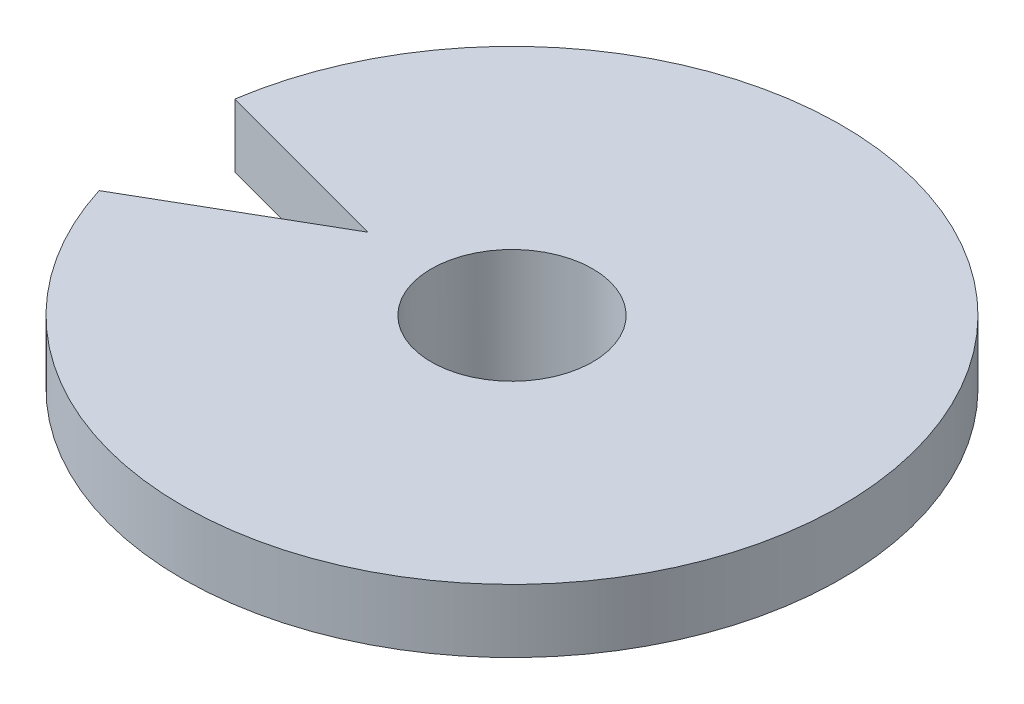
SolidWorks part; units mm, degrees
ref_plane "Front Plane" through (0, 0, 0) normal (0, 0, 1) x (1, 0, 0)
ref_plane "Top Plane" through (0, 0, 0) normal (0, 1, 0) x (1, 0, 0)
ref_plane "Right Plane" through (0, 0, 0) normal (1, 0, 0) x (0, 0, -1)
sketch "Sketch1" plane through (0, 0, 0) normal (0, 1, 0) x (1, 0, 0)
  circle A0 centre (0, 0) radius 5.685
  circle A1 centre (0, 0) radius 3.185
  dimension "D1" = 2.5
  dimension "D2" = 6.37
extrude "Boss-Extrude1" add sketch "Sketch1" along normal blind 4.46
sketch "Sketch2" plane through (0, 4.46, 0) normal (0, 1, 0) x (1, 0, 0)
  circle A0 centre (0, 0) radius 13
extrude "Boss-Extrude2" add sketch "Sketch2" along normal blind 2.5
sketch "Sketch3" plane through (0, 4.46, 0) normal (0, -1, 0) x (1, 0, 0)
  circle A0 centre (0, 0) radius 3.185
extrude "Cut-Extrude1" cut sketch "Sketch3" against normal blind 2.5
sketch "Sketch4" plane through (0, 4.46, 0) normal (0, -1, 0) x (1, 0, 0)
  line L1 (-5.685, 0) -> (-12.4072, 3.881)
  line L2 (-5.685, 0) -> (-12.8572, -1.9218)
  circle A0 centre (0, 0) radius 5.685 construction
  circle A1 centre (0, 0) radius 5.685 construction
  circle A2 centre (0, 0) radius 13 construction
  dimension "D1" = 45
extrude "Cut-Extrude3" cut sketch "Sketch4" against normal through all and the other way through all flip side to cut
